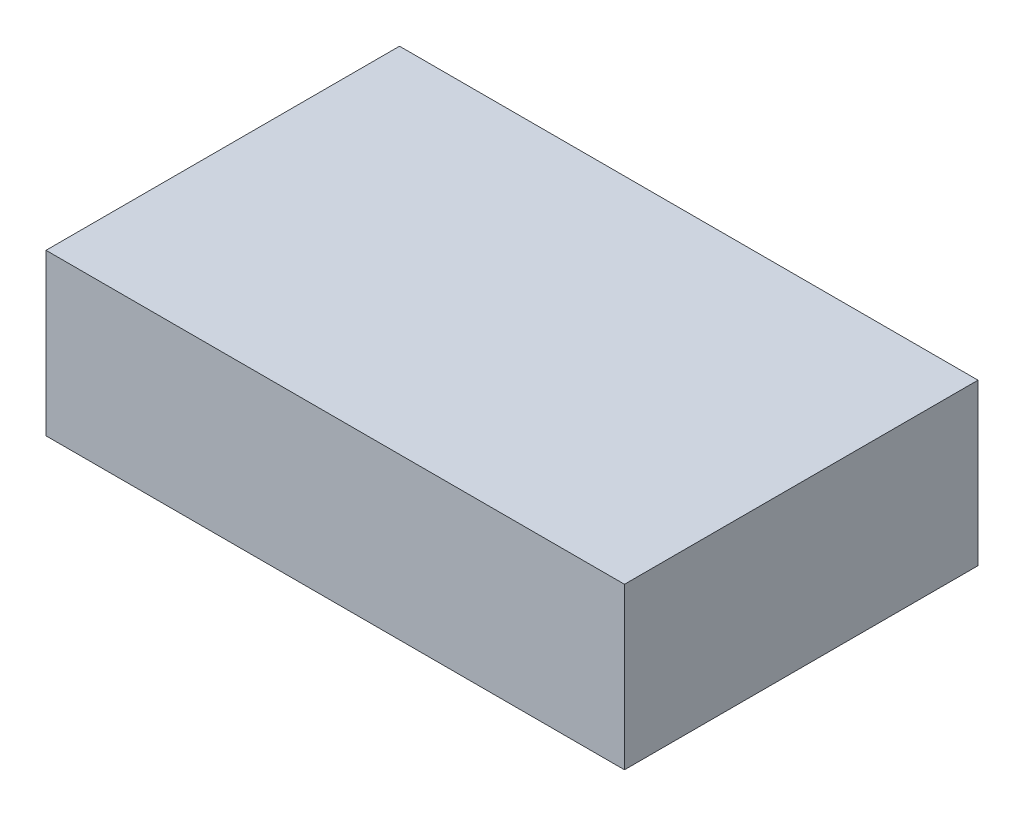
SolidWorks part; units mm, degrees
ref_plane "Front Plane" through (0, 0, 0) normal (0, 0, 1) x (1, 0, 0)
ref_plane "Top Plane" through (0, 0, 0) normal (0, 1, 0) x (1, 0, 0)
ref_plane "Right Plane" through (0, 0, 0) normal (1, 0, 0) x (0, 0, -1)
sketch "Sketch1" plane through (0, 0, 0) normal (0, 1, 0) x (1, 0, 0)
  line L1 (0, 0) -> (36, 0)
  line L2 (0, 0) -> (0, 22)
  line L3 (0, 22) -> (36, 22)
  line L4 (36, 0) -> (36, 22)
  dimension "D1" = 22
  dimension "D2" = 36
extrude "Boss-Extrude1" add sketch "Sketch1" along normal blind 10
